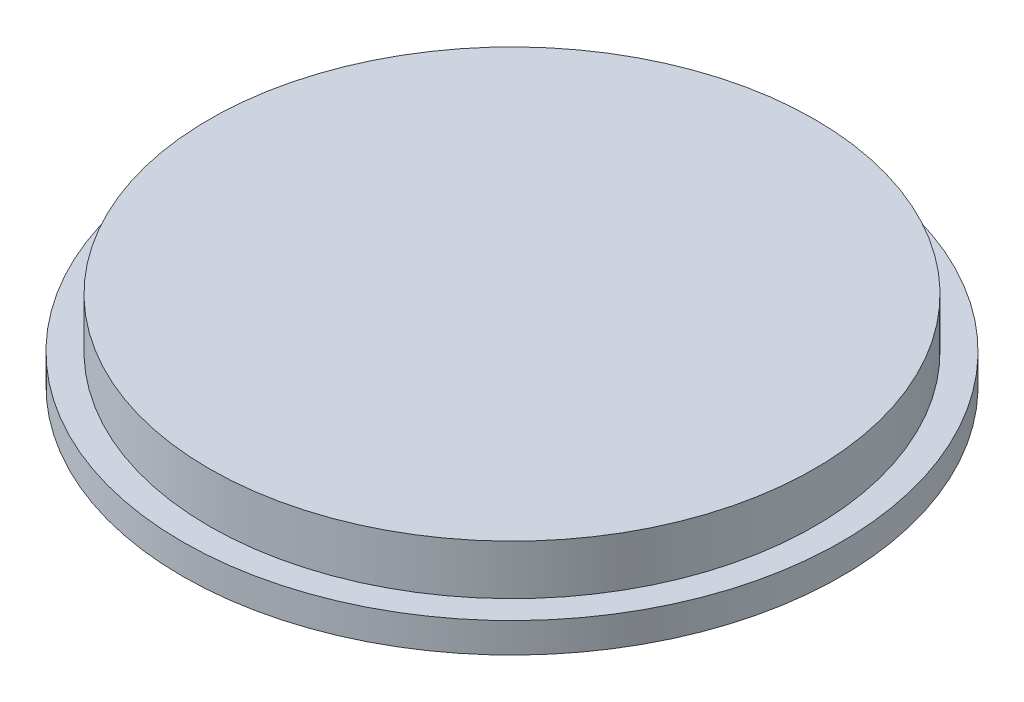
SolidWorks part; units mm, degrees
ref_plane "Front Plane" through (0, 0, 0) normal (0, 0, 1) x (1, 0, 0)
ref_plane "Top Plane" through (0, 0, 0) normal (0, 1, 0) x (1, 0, 0)
ref_plane "Right Plane" through (0, 0, 0) normal (1, 0, 0) x (0, 0, -1)
sketch "Sketch1" plane through (0, 0, 0) normal (0, 1, 0) x (1, 0, 0)
  circle A0 centre (0, 0) radius 33.1
  dimension "D1" = 66.2
extrude "Boss-Extrude1" add sketch "Sketch1" along normal blind 3
sketch "Sketch2" plane through (0, 3, 0) normal (0, 1, 0) x (1, 0, 0)
  circle A0 centre (0, 0) radius 30.4
  dimension "D1" = 60.8
extrude "Boss-Extrude2" add sketch "Sketch2" along normal blind 5
